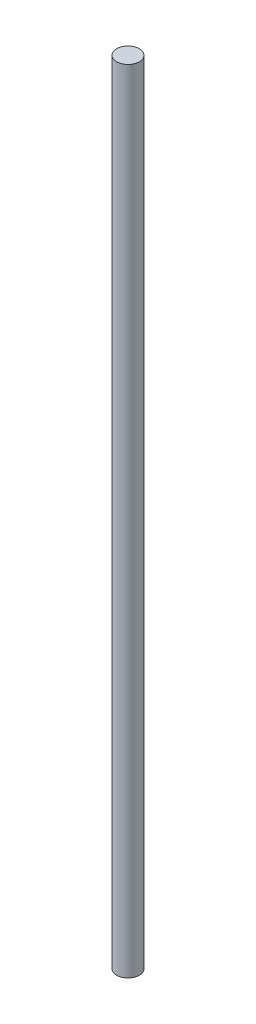
SolidWorks part; units mm, degrees
material "Náilon 6/10"
ref_plane "Plano frontal" through (0, 0, 0) normal (0, 0, 1) x (1, 0, 0)
ref_plane "Plano superior" through (0, 0, 0) normal (0, 1, 0) x (1, 0, 0)
ref_plane "Plano direito" through (0, 0, 0) normal (1, 0, 0) x (0, 0, -1)
sketch "Esboço1" plane through (0, 0, 0) normal (0, 1, 0) x (1, 0, 0)
  circle A0 centre (0, 0) radius 0.5
  dimension "D1" = 1
extrude "Ressalto-extrusão1" add sketch "Esboço1" along normal blind 35
